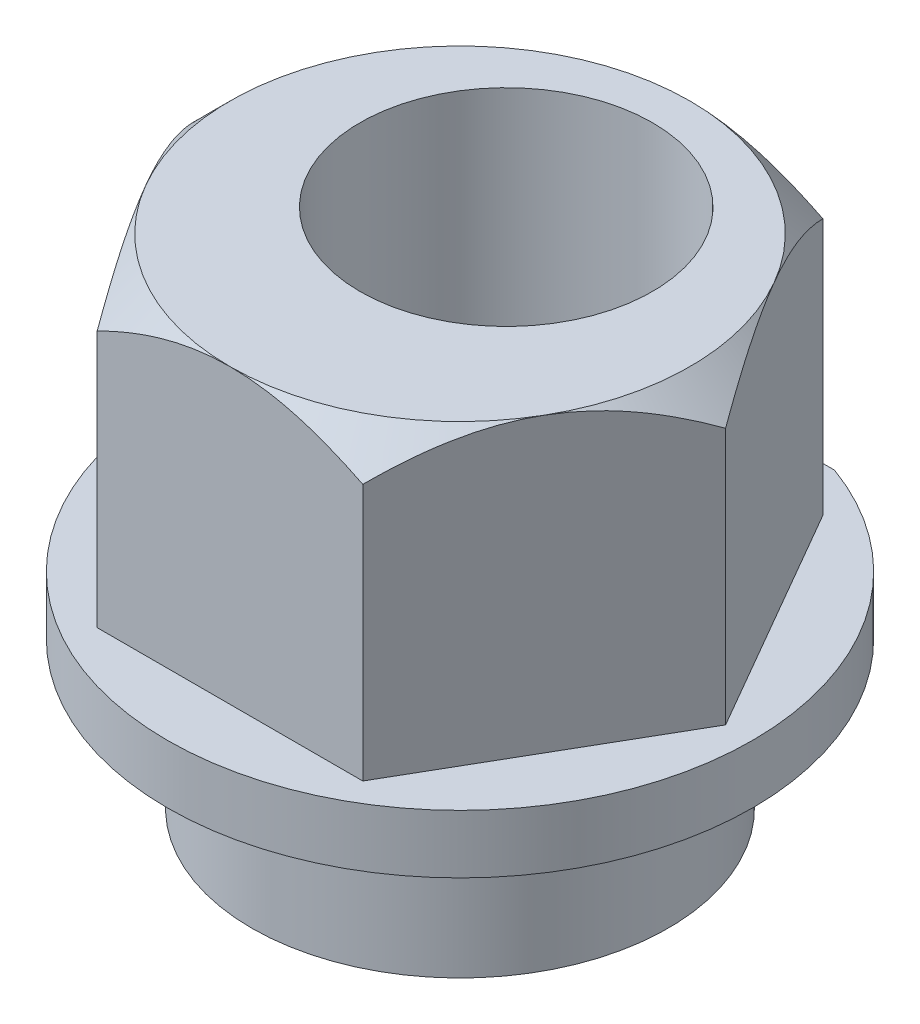
SolidWorks part; units mm, degrees
material "AISI 304"
ref_plane "Front Plane" through (0, 0, 0) normal (0, 0, 1) x (1, 0, 0)
ref_plane "Top Plane" through (0, 0, 0) normal (0, 1, 0) x (1, 0, 0)
ref_plane "Right Plane" through (0, 0, 0) normal (1, 0, 0) x (0, 0, -1)
sketch "Sketch2" plane through (0, 0, 0) normal (0, 1, 0) x (1, 0, 0)
  line L1 (2.27, -3.9318) -> (4.54, 0)
  line L2 (4.54, 0) -> (2.27, 3.9318)
  line L3 (2.27, 3.9318) -> (-2.27, 3.9318)
  line L4 (-2.27, 3.9318) -> (-4.54, 0)
  line L5 (-4.54, 0) -> (-2.27, -3.9318)
  line L6 (-2.27, -3.9318) -> (2.27, -3.9318)
  circle A0 centre (0, 0) radius 3.9318 construction
  dimension "D1" = 4.54
extrude "Boss-Extrude1" add sketch "Sketch2" along normal blind 5
sketch "Sketch3" plane through (0, 5, 0) normal (0, 1, 0) x (1, 0, 0)
  circle A0 centre (0, 0) radius 3.9318
extrude "Cut-Extrude1" cut sketch "Sketch3" against normal blind 5 draft 45 flip side to cut
sketch "Sketch4" plane through (0, 0, 0) normal (0, -1, 0) x (1, 0, 0)
  line L0 (-1.7, -4.7021) -> (1.7, -4.7021)
  arc A0 (1.7, -4.7021) -> (-1.7, -4.7021) centre (0, 0) ccw
  dimension "D1" = 5
  dimension "D2" = 3.4
extrude "Boss-Extrude2" add sketch "Sketch4" along normal blind 1
sketch "Sketch5" plane through (0, -1, 0) normal (0, -1, 0) x (1, 0, 0)
  circle A0 centre (0, 0) radius 3.56
  dimension "D1" = 7.12
extrude "Boss-Extrude3" add sketch "Sketch5" along normal blind 2.5
sketch "Sketch6" plane through (0, -3.5, 0) normal (0, -1, 0) x (1, 0, 0)
  circle A0 centre (0, -0.79) radius 2.5
  dimension "D2" = 5
  dimension "D1" = 0.79
extrude "Cut-Extrude2" cut sketch "Sketch6" against normal through all
